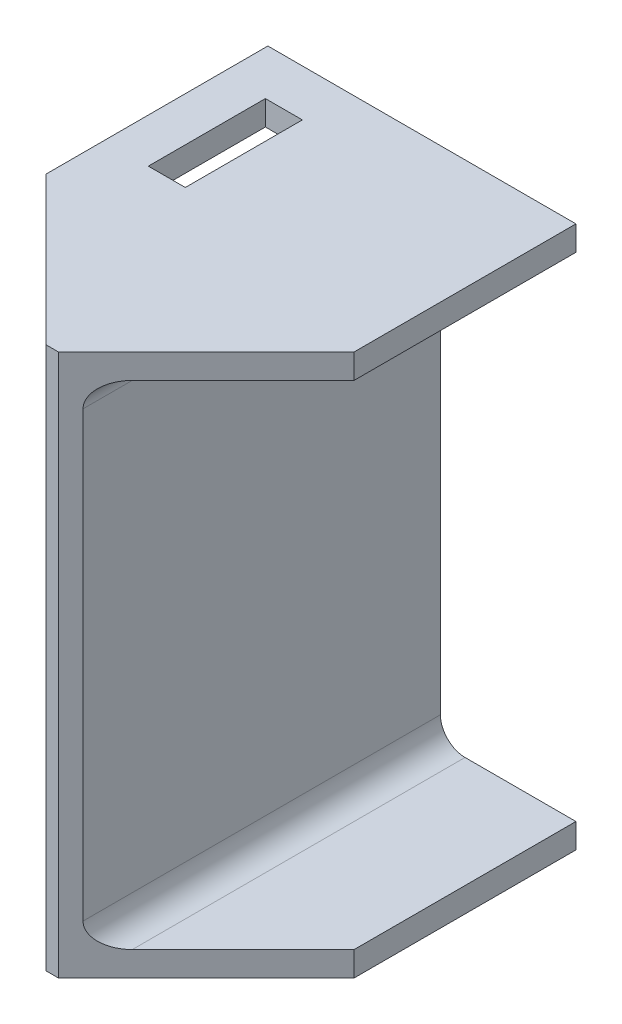
SolidWorks part; units mm, degrees
ref_plane "Front Plane" through (0, 0, 0) normal (0, 0, 1) x (1, 0, 0)
ref_plane "Top Plane" through (0, 0, 0) normal (0, 1, 0) x (1, 0, 0)
ref_plane "Right Plane" through (0, 0, 0) normal (1, 0, 0) x (0, 0, -1)
sketch "Sketch1" plane through (0, 0, 0) normal (0, 0, 1) x (1, 0, 0)
  line L0 (6.8614, 34.9263) -> (17.8614, 34.9263)
  line L1 (-7.1386, 36.9263) -> (17.8614, 36.9263)
  line L2 (-7.1386, 36.9263) -> (-7.1386, 34.9263)
  line L3 (-7.1386, 34.9263) -> (3.8614, 34.9263)
  line L4 (17.8614, 36.9263) -> (17.8614, 34.9263)
  line L5 (6.8614, -5.0737) -> (17.8614, -5.0737)
  line L6 (3.8614, 34.9263) -> (3.8614, -5.0737)
  line L8 (6.8614, 34.9263) -> (6.8614, -5.0737)
  line L9 (-7.1386, -5.0737) -> (3.8614, -5.0737)
  line L10 (-7.1386, -5.0737) -> (-7.1386, -7.0737)
  line L11 (-7.1386, -7.0737) -> (17.8614, -7.0737)
  line L12 (17.8614, -5.0737) -> (17.8614, -7.0737)
  dimension "D1" = 25
  dimension "D2" = 25
  dimension "D3" = 11
  dimension "D4" = 11
  dimension "D5" = 2
  dimension "D6" = 2
  dimension "D8" = 0
  dimension "D9" = 40
extrude "Boss-Extrude1" add sketch "Sketch1" along normal blind 30
chamfer "Chamfer1" distance 12 angle 45 2 edges at (-7.1386, 35.9263, 30) (17.8614, 35.9263, 30)
fillet "Fillet1" radius 2 4 edges at (6.8614, 34.9263, 14.5) (3.8614, 34.9263, 14.5) (3.8614, -5.0737, 14.5) (6.8614, -5.0737, 14.5)
sketch "Sketch2" plane through (0, 36.9263, 0) normal (0, 1, 0) x (1, 0, 0)
  line L1 (-0.5455, -13.2945) -> (-3.5455, -13.2945)
  line L2 (-0.5455, -13.2945) -> (-0.5455, -3.7945)
  line L3 (-0.5455, -3.7945) -> (-3.5455, -3.7945)
  line L4 (-3.5455, -13.2945) -> (-3.5455, -3.7945)
  dimension "D1" = 9.5
  dimension "D2" = 3
extrude "Cut-Extrude1" cut sketch "Sketch2" against normal blind 30
